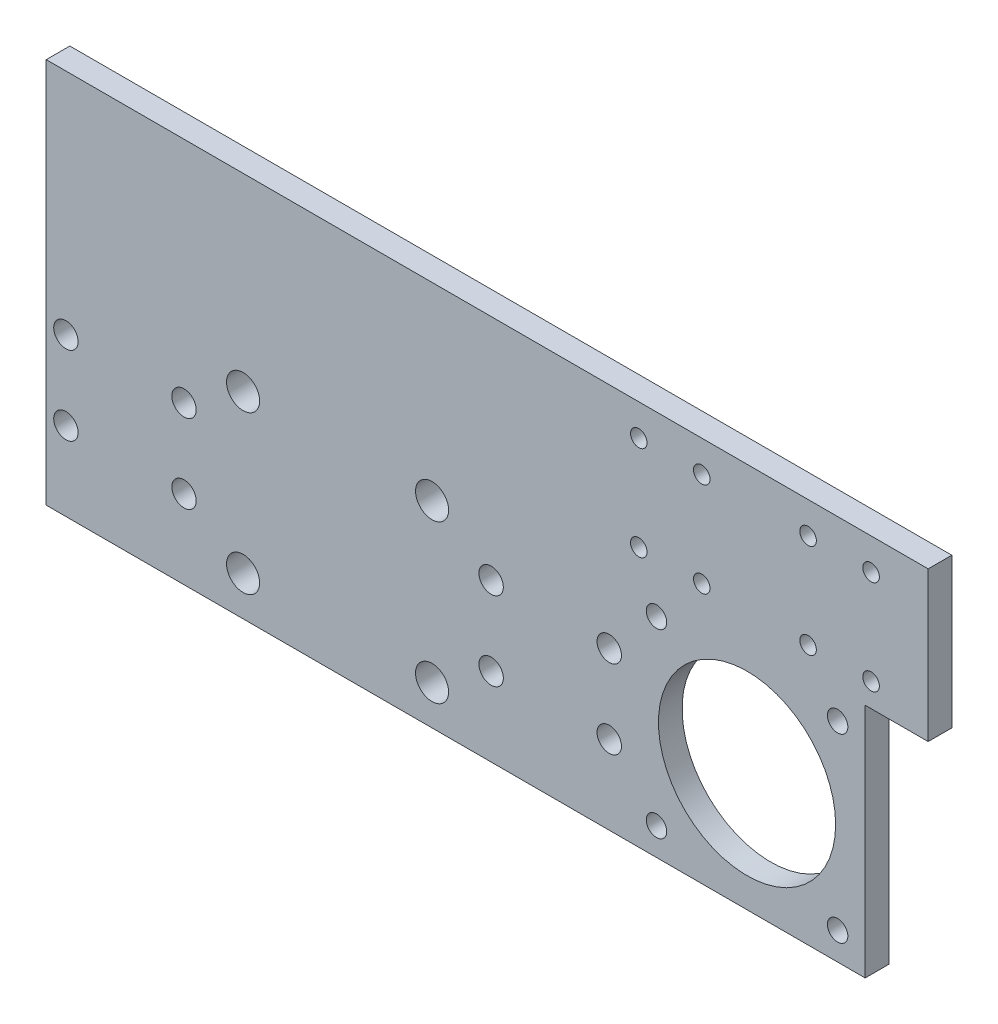
SolidWorks part; units mm, degrees
material "Thornel Mat VMA"
ref_plane "前视基准面" through (0, 0, 0) normal (0, 0, 1) x (1, 0, 0)
ref_plane "上视基准面" through (0, 0, 0) normal (0, 1, 0) x (1, 0, 0)
ref_plane "右视基准面" through (0, 0, 0) normal (1, 0, 0) x (0, 0, -1)
sketch "草图1" plane through (0, 0, 0) normal (0, 0, 1) x (1, 0, 0)
  line L1 (-37, 15) -> (37, 15)
  line L2 (-37, 15) -> (-37, -15)
  line L3 (-37, -15) -> (37, -15)
  line L4 (37, 15) -> (37, -15)
  line L5 (-37, 15) -> (37, -15) construction
  line L6 (-37, -15) -> (37, 15) construction
  point P0 (0, 0)
  dimension "D1" = 74
  dimension "D2" = 30
extrude "凸台-拉伸1" add sketch "草图1" along normal blind 3
ref_plane "基准面1" through (0, 0, 0) normal (0, 0, -1) x (-1, 0, 0)
sketch "草图2" plane through (0, 0, 0) normal (0, 0, -1) x (-1, 0, 0)
  circle A0 centre (-34.5, 5) radius 1.55
  circle A1 centre (-34.5, -5) radius 1.55
  circle A2 centre (-19.5, 5) radius 1.55
  circle A3 centre (-19.5, -5) radius 1.55
  circle A4 centre (-12, 10) radius 2.1
  circle A5 centre (12, 10) radius 2.1
  circle A6 centre (-12, -10) radius 2.1
  circle A7 centre (12, -10) radius 2.1
  circle A8 centre (34.5, 5) radius 1.55
  circle A9 centre (34.5, -5) radius 1.55
  circle A10 centre (19.5, 5) radius 1.55
  circle A11 centre (19.5, -5) radius 1.55
extrude "切除-拉伸1" cut sketch "草图2" against normal blind 3
ref_plane "基准面2" through (0, 0, 3) normal (0, 0, 1) x (1, 0, 0)
ref_plane "基准面3" through (0, 0, 3) normal (0, 0, 1) x (1, 0, 0)
sketch "草图3" plane through (0, 0, 3) normal (0, 0, 1) x (1, 0, 0)
  line L1 (37, 15) -> (67, 15)
  line L2 (37, 15) -> (37, -15)
  line L3 (37, -15) -> (67, -15)
  line L4 (67, 15) -> (67, -15)
  circle A0 centre (52, 0) radius 11.25
  circle A1 centre (40.5, 11.5) radius 1.3
  circle A2 centre (63.5, 11.5) radius 1.3
  circle A3 centre (40.5, -11.5) radius 1.3
  circle A4 centre (63.5, -11.5) radius 1.3
  dimension "D2" = 2.6
  dimension "D3" = 2.6
  dimension "D4" = 2.6
  dimension "D5" = 2.6
  dimension "D6" = 22.5
  dimension "D1" = 30
extrude "凸台-拉伸2" add sketch "草图3" against normal blind 3
sketch "草图4" plane through (0, 0, 3) normal (0, 0, 1) x (1, 0, 0)
  line L1 (-37, 15) -> (37, 15)
  line L2 (-37, 15) -> (-37, 34)
  line L3 (-37, 34) -> (37, 34)
  line L4 (37, 15) -> (37, 34)
extrude "凸台-拉伸3" add sketch "草图4" against normal through all
sketch "草图5" plane through (0, 0, 3) normal (0, 0, 1) x (1, 0, 0)
  circle A0 centre (-21.5, 31.5) radius 1.05
  circle A1 centre (-21.5, 16.5) radius 1.05
  circle A2 centre (-11.5, 31.5) radius 1.05
  circle A3 centre (-11.5, 16.5) radius 1.05
  circle A4 centre (27, 31.5) radius 1.05
  circle A5 centre (17, 31.5) radius 1.05
  circle A6 centre (17, 16.5) radius 1.05
  circle A7 centre (27, 16.5) radius 1.05
  dimension "D1" = 2.1
  dimension "D2" = 2.1
  dimension "D3" = 2.1
  dimension "D4" = 2.1
  dimension "D5" = 2.1
  dimension "D6" = 2.1
  dimension "D7" = 2.1
  dimension "D8" = 2.1
extrude "切除-拉伸2" cut sketch "草图5" against normal blind 10
sketch "草图6" plane through (0, 0, 3) normal (0, 0, 1) x (1, 0, 0)
  line L0 (-21.5, 31.5) -> (-11.5, 16.5) construction
  line L1 (17, 31.5) -> (27, 16.5) construction
  line L2 (-20.5, 30) -> (-12.5, 30) construction
  line L3 (-20.5, 30) -> (-20.5, 18) construction
  line L4 (-20.5, 18) -> (-12.5, 18) construction
  line L5 (-12.5, 30) -> (-12.5, 18) construction
  line L6 (-20.5, 30) -> (-12.5, 18) construction
  line L7 (-20.5, 18) -> (-12.5, 30) construction
  line L10 (18, 30) -> (26, 30) construction
  line L11 (18, 30) -> (18, 18) construction
  line L12 (18, 18) -> (26, 18) construction
  line L13 (26, 30) -> (26, 18) construction
  line L14 (18, 30) -> (26, 18) construction
  line L15 (18, 18) -> (26, 30) construction
  circle A0 centre (-20.5, 30) radius 1.05
  circle A1 centre (-12.5, 30) radius 1.05
  circle A2 centre (-12.5, 18) radius 1.05
  circle A3 centre (-20.5, 18) radius 1.05
  circle A4 centre (18, 30) radius 1.05
  circle A9 centre (26, 30) radius 1.05
  circle A10 centre (26, 18) radius 1.05
  circle A11 centre (18, 18) radius 1.05
  point P4 (-16.5, 24)
  point P17 (22, 24)
  point P21 (-14.6838, 21.3073)
  dimension "D3" = 2.1
  dimension "D4" = 2.1
  dimension "D5" = 2.1
  dimension "D6" = 2.1
  dimension "D9" = 2.1
  dimension "D10" = 2.1
  dimension "D11" = 2.1
  dimension "D12" = 2.1
  dimension "D1" = 8
  dimension "D2" = 12
  dimension "D7" = 12
  dimension "D8" = 8
extrude "切除-拉伸4" cut sketch "草图6" against normal blind 10
ref_plane "基准面4" through (0, 15, 0) normal (0, 1, 0) x (1, 0, 0)
sketch "草图7" plane through (0, 15, 0) normal (0, 1, 0) x (1, 0, 0)
  line L1 (37, -3) -> (67, -3)
  line L2 (37, -3) -> (37, 0)
  line L3 (37, 0) -> (67, 0)
  line L4 (67, -3) -> (67, 0)
extrude "凸台-拉伸4" add sketch "草图7" along normal through all
sketch "草图10" plane through (0, 0, 0) normal (0, 0, -1) x (-1, 0, 0)
  line L0 (55, 15) -> (-55, 15) construction
  line L1 (-67, 34) -> (-75, 34)
  line L2 (-67, 34) -> (-67, 15)
  line L3 (-67, 15) -> (-75, 15)
  line L4 (-75, 34) -> (-75, 15)
  dimension "D1" = 8
extrude "凸台-拉伸6" add sketch "草图10" against normal blind 3
sketch "草图11" plane through (0, 0, 3) normal (0, 0, 1) x (1, 0, 0)
  circle A0 centre (59.75, 30) radius 1.05
  circle A1 centre (67.75, 30) radius 1.05
  circle A6 centre (59.75, 18) radius 1.05
  circle A7 centre (67.75, 18) radius 1.05
  dimension "D1" = 2.1
  dimension "D2" = 2.1
  dimension "D3" = 2.1
  dimension "D4" = 2.1
extrude "切除-拉伸5" cut sketch "草图11" against normal blind 10
sketch "草图12" plane through (0, 0, 0) normal (0, 0, 1) x (1, 0, 0)
  line L0 (55, 15) -> (-55, 15) construction
  line L1 (-37, 34) -> (35.682, 34)
  line L2 (-37, 34) -> (-37, 15)
  line L3 (-37, 15) -> (35.682, 15)
  line L4 (35.682, 34) -> (35.682, 15)
extrude "凸台-拉伸7" add sketch "草图12" along normal blind 3
sketch "草图13" plane through (0, 0, 0) normal (0, 0, 1) x (1, 0, 0)
  line L0 (75, 34) -> (-37, 34) construction
  line L1 (38.25, 30) -> (46.25, 30) construction
  line L2 (38.25, 30) -> (38.25, 18) construction
  line L3 (38.25, 18) -> (46.25, 18) construction
  line L4 (46.25, 30) -> (46.25, 18) construction
  line L5 (38.25, 30) -> (46.25, 18) construction
  line L6 (38.25, 18) -> (46.25, 30) construction
  circle A1 centre (59.75, 18) radius 1.05 construction
  circle A2 centre (46.25, 30) radius 1.05
  circle A3 centre (46.25, 18) radius 1.05
  circle A4 centre (38.25, 18) radius 1.05
  circle A5 centre (38.25, 30) radius 1.05
  point P0 (42.25, 24)
  dimension "D5" = 2.1
  dimension "D6" = 2.1
  dimension "D7" = 2.1
  dimension "D8" = 2.1
  dimension "D1" = 8
  dimension "D2" = 12
  dimension "D3" = 4
  dimension "D4" = 13.5
extrude "切除-拉伸7" cut sketch "草图13" along normal blind 3
